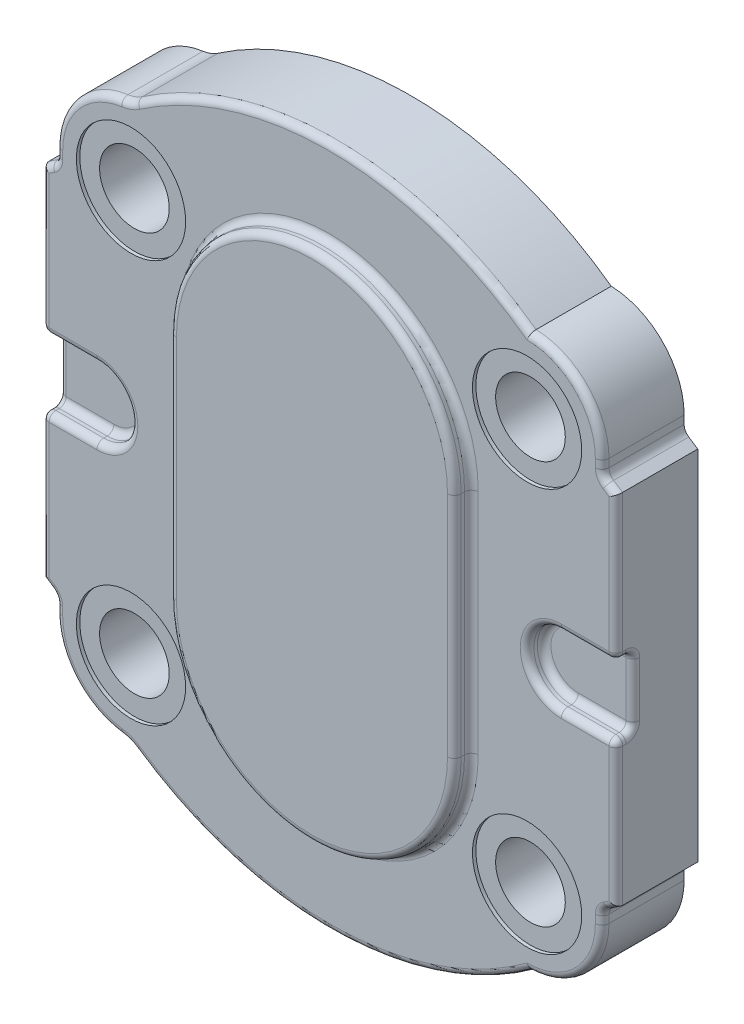
SolidWorks part; units mm, degrees
ref_plane "Ön Düzlem" through (0, 0, 0) normal (0, 0, 1) x (1, 0, 0)
ref_plane "Üst Düzlem" through (0, 0, 0) normal (0, 1, 0) x (1, 0, 0)
ref_plane "Sağ Düzlem" through (0, 0, 0) normal (1, 0, 0) x (0, 0, -1)
sketch "Çizim1" plane through (0, 0, 0) normal (0, 0, 1) x (1, 0, 0)
  line L0 (0, -50) -> (0, -61.4782) construction
  line L1 (0, 61.4782) -> (0, 50) construction
  line L2 (-40, 29.5) -> (-40, 28.306)
  line L3 (-40.6776, 27.0515) -> (-42, 26.1845)
  line L4 (-42, 26.1845) -> (-42, -26.1845)
  line L5 (40.6776, 27.0515) -> (42, 26.1845)
  line L6 (40, 29.5) -> (40, 28.306)
  line L7 (42, 26.1845) -> (42, -26.1845)
  line L8 (-40.6776, -27.0515) -> (-42, -26.1845)
  line L9 (-40, -29.5) -> (-40, -28.306)
  line L10 (40, -29.5) -> (40, -28.306)
  line L11 (40.6776, -27.0515) -> (42, -26.1845)
  arc A4 (-28.2748, 41.2375) -> (29.3283, 40.4951) centre (0, 0) cw
  circle A5 centre (-29, 29.5) radius 5.1
  circle A6 centre (29, 29.5) radius 5.1
  arc A7 (-30.4453, 40.4046) -> (-40, 29.5) centre (-29, 29.5) ccw
  arc A8 (29.3283, 40.4951) -> (39.9168, 28.1493) centre (29, 29.5) cw
  arc A9 (-40, 28.306) -> (-40.6776, 27.0515) centre (-41.5, 28.306) cw
  arc A10 (-28.2748, 41.2375) -> (-30.4453, 40.4046) centre (-31.1023, 45.3613) cw
  arc A11 (28.2748, 41.2375) -> (30.4453, 40.4046) centre (31.1023, 45.3613) ccw
  arc A12 (40, 28.306) -> (40.6776, 27.0515) centre (41.5, 28.306) ccw
  arc A13 (30.4453, 40.4046) -> (40, 29.5) centre (29, 29.5) cw
  arc A14 (-28.2748, -41.2375) -> (29.3283, -40.4951) centre (0, 0) ccw
  arc A15 (-28.2748, -41.2375) -> (-30.4453, -40.4046) centre (-31.1023, -45.3613) ccw
  arc A16 (-40, -28.306) -> (-40.6776, -27.0515) centre (-41.5, -28.306) ccw
  arc A17 (-30.4453, -40.4046) -> (-40, -29.5) centre (-29, -29.5) cw
  circle A18 centre (-29, -29.5) radius 5.1
  arc A19 (30.4453, -40.4046) -> (40, -29.5) centre (29, -29.5) ccw
  arc A20 (40, -28.306) -> (40.6776, -27.0515) centre (41.5, -28.306) cw
  arc A21 (28.2748, -41.2375) -> (30.4453, -40.4046) centre (31.1023, -45.3613) cw
  arc A22 (29.3283, -40.4951) -> (39.9168, -28.1493) centre (29, -29.5) ccw
  circle A23 centre (29, -29.5) radius 5.1
  point P11 (0, 0)
  point P13 (0, 0)
  point P16 (0, 0)
  point P24 (-29.3283, -40.4951)
  point P65 (-42, 0)
  point P77 (42, 0)
  dimension "D2" = 39.9168
  dimension "D3" = 40.6776
  dimension "D5" = 10.2
  dimension "D6" = 58
  dimension "D9" = 50
  dimension "D10" = 11
  dimension "D11" = 42
  dimension "D12" = 1.5
  dimension "D13" = 5
  dimension "D4" = 26.1845
  dimension "D8" = 29.5
extrude "Yükseklik-Ekstrüzyon1" add sketch "Çizim1" along normal blind 12
sketch "Çizim2" plane through (0, 0, 12) normal (0, 0, 1) x (1, 0, 0)
  line L0 (0, 57.9286) -> (0, -4.17) construction
  line L1 (-82.158, 0) -> (-20.85, 0) construction
  line L2 (20.85, -16.68) -> (20.85, 16.68)
  line L3 (-20.85, -16.68) -> (-20.85, 16.68)
  line L4 (20.85, 0) -> (82.158, 0) construction
  line L5 (0, -37.53) -> (0, -57.9286) construction
  arc A0 (20.85, 16.68) -> (-20.85, 16.68) centre (0, 16.68) ccw
  arc A1 (-20.85, -16.68) -> (20.85, -16.68) centre (0, -16.68) ccw
  point P4 (0, 0)
  point P8 (0, 0)
  point P18 (0, 37.53)
  dimension "D1" = 41.7
  dimension "D2" = 16.68
  dimension "D3" = 16.68
  dimension "D4" = 37.53
extrude "Yükseklik-Ekstrüzyon3" add sketch "Çizim2" along normal blind 2.5
sketch "Çizim5" plane through (0, 0, 12) normal (0, 0, 1) x (1, 0, 0)
  line L1 (-34, 5.0729) -> (-45.4313, 5.0729)
  line L2 (-34, -4.9271) -> (-45.4313, -4.9271)
  line L4 (34, 5) -> (44.1908, 5)
  line L5 (34, -5) -> (44.1908, -5)
  line L8 (44.1908, 5) -> (44.1908, -5)
  line L9 (-45.4313, -4.9271) -> (-45.4313, 5.0729)
  arc A0 (-34, -4.9271) -> (-34, 5.0729) centre (-34, 0.0729) ccw
  arc A1 (34, -5) -> (34, 5) centre (34, 0) cw
  point P11 (0, 0)
  point P22 (0, 0)
  dimension "D2" = 5
extrude "Kes-Ekstrüzyon3" cut sketch "Çizim5" against normal blind 2.5
sketch "Çizim6" plane through (0, 0, 12) normal (0, 0, 1) x (1, 0, 0)
  circle A0 centre (-29, 29.5) radius 8
  circle A1 centre (-29, -29.5) radius 8
  circle A2 centre (29, 29.5) radius 8
  circle A3 centre (29, -29.5) radius 8
  dimension "D1" = 16
extrude "Kes-Ekstrüzyon4" cut sketch "Çizim6" against normal blind 0.5
fillet "Radyus1" radius 1 50 edges at (29, 0, 12) (38, -5, 12) (42, -15.5923, 12) (41.3388, -26.618, 12) (40.1802, -27.5931, 12) (40, -28.903, 12) (36.8934, -37.1612, 12) (0.6444, -49.9958, 12) (-29.311, -40.6932, 12) (-37.2734, -36.7492, 12) (-40, -28.903, 12) (-40.1802, -27.5931, 12) (-41.3388, -26.618, 12) (-42, -15.5558, 12) (-38, -4.9271, 12) (-29, 0.0729, 12) (-38, 5.0729, 12) (-42, 15.6287, 12) (-41.3388, 26.618, 12) (-40.1802, 27.5931, 12) (-40, 28.903, 12) (-37.2734, 36.7492, 12) (-29.311, 40.6932, 12) (36.8934, 37.1612, 12) (40, 28.903, 12) (40.1802, 27.5931, 12) (41.3388, 26.618, 12) (42, 15.5923, 12) (38, 5, 12) (0.6444, 49.9958, 12) (42, -5, 10.75) (42, 5, 10.75) (-42, 5.0729, 10.75) (-42, -4.9271, 10.75) (38, -5, 9.5) (29, 0, 9.5) (38, 5, 9.5) (42, 0, 9.5) (-38, 5.0729, 9.5) (-29, 0.0729, 9.5) (-38, -4.9271, 9.5) (-42, 0.0729, 9.5) (20.85, 0, 12) (0, -37.53, 12) (-20.85, 0, 12) (0, 37.53, 14.5) (-20.85, 0, 14.5) (0, -37.53, 14.5) (20.85, 0, 14.5) (0, 37.53, 12)
